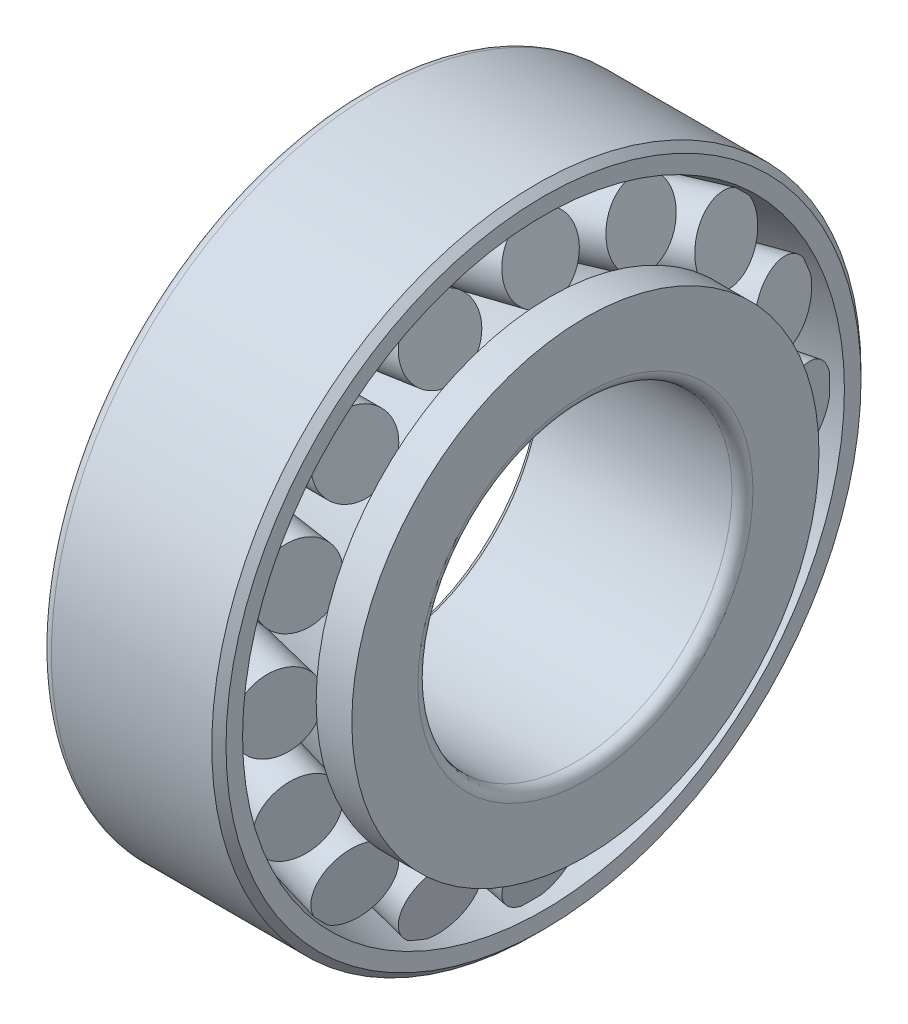
SolidWorks part; units mm, degrees
revolve "OuterRace" add sketch "OutRacSke" angle 360 about L5
sketch "OutRacSke" plane through (0, 0, 0) normal (0, 0, 1) x (1, 0, 0)
  line L0 (-4, 28.7359) -> (-21, 24.491)
  line L1 (-21, 24.491) -> (-21, 30)
  line L2 (-20, 31) -> (-4.68, 31)
  line L3 (-4.68, 31) -> (-4, 30.32)
  line L4 (-4, 30.32) -> (-4, 28.7359)
  line L5 (-42.5, 0) -> (42.5, 0) construction
  arc A0 (-21, 30) -> (-20, 31) centre (-20, 30) cw
  dimension "cup_radius" = 1
  dimension "OD" = 62
  dimension "cup_width" = 17
  dimension "Tangle" = 14.02
  dimension "offset" = 21
  dimension "chamfer" = 0.68
  dimension "D8" = 45
  dimension "cup_SID" = 48.982
ref_plane "Plane1" through (0, 0, 0) normal (0, 0, 1) x (1, 0, 0)
ref_plane "Plane2" through (0, 0, 0) normal (0, 1, 0) x (1, 0, 0)
ref_plane "Plane3" through (0, 0, 0) normal (1, 0, 0) x (0, 0, -1)
sketch "Clipboard" plane through (0, 0, 0) normal (0, 0, 1) x (1, 0, 0)
  line L0 (0, 0) -> (10, 0) construction
  line L1 (0, 0) -> (47.0845, -13.5013)
  line L2 (0, 0) -> (28.8379, 8.2691)
  line L3 (0, 0) -> (59.5982, -17.0895)
  line L4 (0, 0) -> (-15.2977, -0.267)
  line L5 (0, 0) -> (-7.2, 21)
  dimension "Bore" = 30
  dimension "Count" = 16
  dimension "Show_count" = 16
  dimension "Max_count" = 16
  dimension "Min_count" = 1
  dimension "Race_OD" = 62
  dimension "Race_ID" = 48.982
  dimension "cyl_len" = 15.3
  dimension "Roller_diameter" = 7.2
  dimension "OA_width" = 21
sketch "RolDetSke" plane through (0, 0, 0) normal (0, 0, 1) x (1, 0, 0)
  line L0 (-19.1279, 21.3716) -> (-20, 24.8644)
  line L1 (-19.1279, 21.3716) -> (-4.2836, 25.0782)
  line L2 (-5.1558, 28.571) -> (-4.2836, 25.0782)
  line L4 (-40.1979, 16.1105) -> (9.681, 28.5652) construction
  line L5 (-5.1558, 28.571) -> (-20, 24.8644)
  line L9 (-4, 28.7359) -> (-21, 24.491) construction
  dimension "cyl_len" = 15.3
  dimension "Roller_diameter" = 7.2
  dimension "dy" = 24.8644
  dimension "D2" = 20
revolve "RollerDetailed" add sketch "RolDetSke" angle 360 about L4
sketch "RolSimSke" [suppressed] plane through (0, 0, 0) normal (0, 0, 1) x (1, 0, 0)
  line L0 (0, 0) -> (-32, 0) construction
  line L1 (-18.5, 33.4057) -> (-4.529, 36.8943)
  line L2 (-18.5, 33.4057) -> (-16.3197, 24.6738)
  line L3 (-16.3197, 24.6738) -> (-2.3486, 28.1624)
  line L4 (-4.529, 36.8943) -> (-2.3486, 28.1624)
  dimension "Tangle" = 14.02
  dimension "Roller_diameter" = 7.2
  dimension "dy" = 24.8644
  dimension "dx" = 20
revolve "RollersSimplified" [suppressed] add sketch "RolSimSke" angle 360 about L0
ref_axis "Axis1" through (-50, 0, 0) along (1, 0, 0)
pattern_circular "RollersDetailed" count 16 every 22.5 about axis through (-50, 0, 0) along (1, 0, 0) of "RollerDetailed", "OuterRace"
sketch "InsRacSke" plane through (0, 0, 0) normal (0, 0, 1) x (1, 0, 0)
  line L0 (-18.3369, 18.2389) -> (-20, 18.2389)
  line L1 (-21, 30) -> (-21, -30) construction
  line L2 (-20, 18.2389) -> (-20, 15.68)
  line L3 (-20, 15.68) -> (-19.32, 15)
  line L4 (-19.32, 15) -> (-1, 15)
  line L5 (0, 16) -> (0, 22.3055)
  line L6 (0, 22.3055) -> (-3.4028, 22.3055)
  line L7 (-3.4028, 22.3055) -> (-3.4028, 21.5855)
  line L8 (-3.4028, 21.5855) -> (-18.247, 17.8789)
  line L9 (-18.247, 17.8789) -> (-18.3369, 18.2389)
  line L10 (-42.5, 0) -> (42.5, 0) construction
  arc A0 (-1, 15) -> (0, 16) centre (-1, 16) ccw
  dimension "Tangle" = 14.02
  dimension "chamfer" = 0.68
  dimension "Bore" = 30
  dimension "cyl_len" = 15.3
  dimension "dy" = 17.8789
  dimension "dx" = 18.247
  dimension "D11" = 45
  dimension "D2" = 21
revolve "InnerRace" add sketch "InsRacSke" angle 360 about L10
sketch "CagSpiSke" [suppressed] plane through (0, 0, 0) normal (0, 0, 1) x (1, 0, 0)
  line L3 (-2.7402, 32.5366) -> (-17.4098, 28.8736)
  line L4 (-17.8466, 28.1461) -> (-17.5559, 26.9819)
  line L6 (-42.5, 0) -> (42.5, 0) construction
  arc A1 (-17.4098, 28.8736) -> (-17.8466, 28.1461) centre (-17.2645, 28.2915) ccw
  dimension "Tangle" = 14.02
  dimension "radius" = 0.48
  dimension "dx" = 19.1279
  dimension "dy" = 21.2479
  dimension "offset" = 1.44
revolve "CageSpine" [suppressed] add sketch "CagSpiSke" angle 0.001 about L6
equation "\"OD@OutRacSke\" = \"Race_OD@Clipboard\""
equation "\"cup_SID@OutRacSke\" = \"Race_ID@Clipboard\""
equation "\"chamfer@OutRacSke\" = \"cup_width@OutRacSke\" / 25"
equation "\"offset@OutRacSke\" = \"OA_width@Clipboard\""
equation "\"D2@RolDetSke\" = \"offset@OutRacSke\" - \"cup_radius@OutRacSke\""
equation "\"dy@RolDetSke\" =  ( ( \"Race_ID@Clipboard\" / 2 ) + ( \"cup_radius@OutRacSke\" ) * tan(\"Tangle@OutRacSke\" * 3.141592654/180) ) * 1.005"
equation "\"cyl_len@RolDetSke\" = \"cyl_len@Clipboard\""
equation "\"Roller_diameter@RolDetSke\" = \"Roller_diameter@Clipboard\""
equation "\"dx@RolSimSke\" = \"offset@OutRacSke\" - \"cup_radius@OutRacSke\""
equation "\"dy@RolSimSke\" =  ( ( \"Race_ID@Clipboard\" / 2 ) + ( \"cup_radius@OutRacSke\" ) * tan(\"Tangle@OutRacSke\" * 3.141592654/180) ) * 1.005"
equation "\"Cyl_Len@RolSimSke\" = \"cyl_len@Clipboard\""
equation "\"Roller_diameter@RolSimSke\" = \"Roller_diameter@Clipboard\""
equation "\"Bore@InsRacSke\" = \"Bore@Clipboard\""
equation "\"Tangle@InsRacSke\" = \"Tangle@OutRacSke\""
equation "\"cyl_len@InsRacSke\" = \"cyl_len@Clipboard\""
equation "\"chamfer@InsRacSke\" = \"chamfer@OutRacSke\""
equation "\"D2@InsRacSke\" = \"OA_width@Clipboard\""
equation "\"dx@InsRacSke\" = \"offset@OutRacSke\" - \"cup_radius@OutRacSke\" -  (  \"Roller_diameter@Clipboard\" * 1.005 )  * sin(\"Tangle@InsRacSke\" * 3.141592654/180)"
equation "\"dy@InsRacSke\" = ( ( \"Race_ID@Clipboard\" / 2 ) + ( \"cup_radius@OutRacSke\" ) * tan(\"Tangle@OutRacSke\" * 3.141592654/180) ) * 1.005 -  ( \"Roller_diameter@Clipboard\" )  * cos(\"Tangle@InsRacSke\" * 3.141592654/180) "
equation "\"front_groove@InsRacSke\" = \"Groove_dp@InsRacSke\" / 2"
equation "\"Tangle@CagSpiSke\" = \"Tangle@OutRacSke\""
equation "\"dx@CagSpiSke\" = ( \"offset@OutRacSke\" - \"cup_radius@OutRacSke\" ) -  (  \"Roller_diameter@Clipboard\" / 2  )  * sin(\"Tangle@InsRacSke\" * 3.141592654/180)"
equation "\"dy@CagSpiSke\" = ( ( \"Race_ID@Clipboard\" / 2 ) + ( \"cup_radius@OutRacSke\" ) * tan(\"Tangle@OutRacSke\" * 3.141592654/180) )  -  ( \"Roller_diameter@Clipboard\" / 2 )  * cos(\"Tangle@InsRacSke\" * 3.141592654/180) "
equation "\"length@CagSpiSke\" = \"cyl_len@Clipboard\" * 1.05"
equation "\"offset@CagSpiSke\" = \"Roller_diameter@Clipboard\" / 5"
equation "\"radius@CagSpiSke\" = \"offset@CagSpiSke\" / 3"
equation "\"D3@CageSpine\" = \"Roller_diameter@Clipboard\" / 6"
equation "\"Max_count@Clipboard\" = int( 3.14159265 / atn(( \"Roller_diameter@Clipboard\" / 2) / sqr( \"dy@CagSpiSke\"  *  \"dy@CagSpiSke\" - ( \"Roller_diameter@Clipboard\" / 2) *  ( \"Roller_diameter@Clipboard\" / 2))))"
equation "\"Max_count@Clipboard\" = ((sgn( \"Max_count@Clipboard\" - \"Count@Clipboard\" )-1)*( \"Max_count@Clipboard\" - \"Count@Clipboard\" ))/-2+ \"Count@Clipboard\""
equation "\"Count@RollersDetailed\" = int( \"Show_count@Clipboard\" ) "
equation "\"Count@RollersDetailed\" = ((sgn( \"Count@RollersDetailed\" - \"Max_count@Clipboard\" )-1)*( \"Count@RollersDetailed\" - \"Max_count@Clipboard\" ))/-2+ \"Max_count@Clipboard\""
equation "\"Count@RollersDetailed\" = ((sgn( \"Count@RollersDetailed\" - \"Min_count@Clipboard\" )+1)*( \"Count@RollersDetailed\" - \"Min_count@Clipboard\"))/2 +\"Min_count@Clipboard\""
equation "\"Angle@RollersDetailed\" = 360.0 / \"Max_count@Clipboard\""
equation "\"Angle@CageSpine\" =  \"Angle@RollersDetailed\" * ( \"Count@RollersDetailed\" -1 + int( \"Count@RollersDetailed\" / \"Max_count@Clipboard\" ) )  + 0.001 -  int( \"Count@RollersDetailed\" / \"Max_count@Clipboard\" ) * 0.001"
equation "\"Angle@CageSpine\" =  \"Angle@CageSpine\" * int( \"Min_count@Clipboard\" / 2) + int(1 / \"Min_count@Clipboard\")  * 0.001"
equation "\"Tangle@RolSimSke\" = \"Tangle@OutRacSke\""
